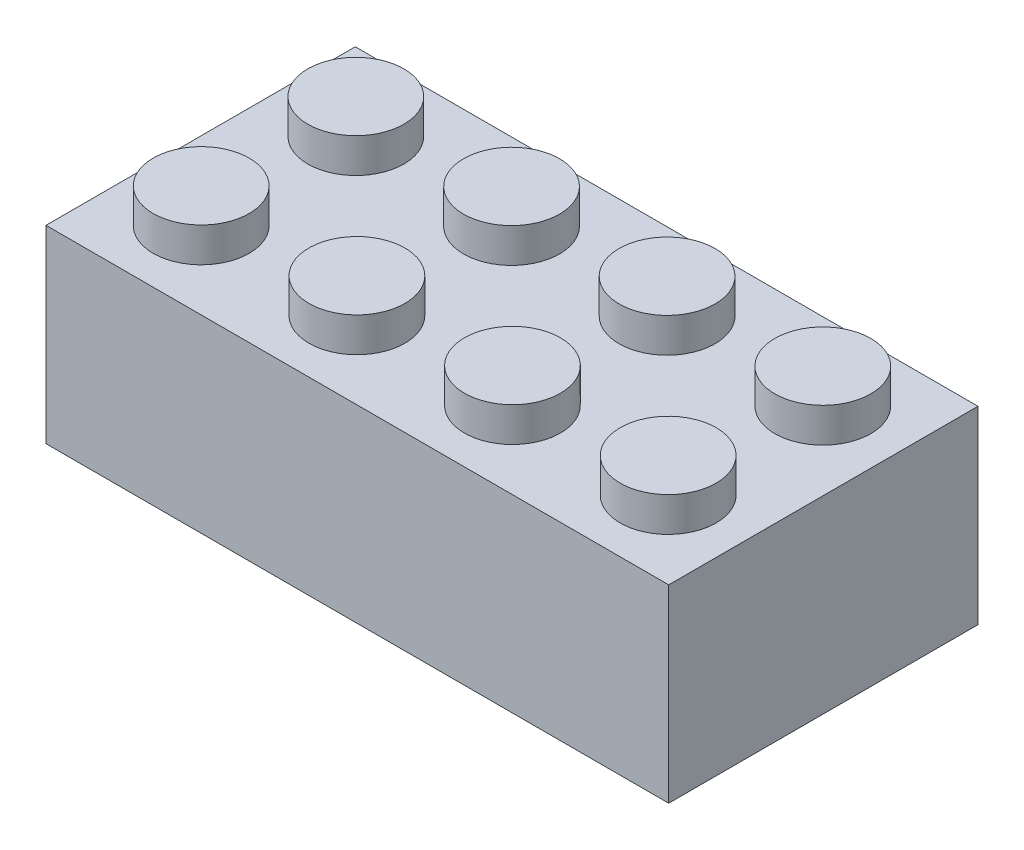
SolidWorks part; units mm, degrees
ref_plane "Front Plane" through (0, 0, 0) normal (0, 0, 1) x (1, 0, 0)
ref_plane "Top Plane" through (0, 0, 0) normal (0, 1, 0) x (1, 0, 0)
ref_plane "Right Plane" through (0, 0, 0) normal (1, 0, 0) x (0, 0, -1)
sketch "Sketch2" plane through (0, 0, 0) normal (0, 1, 0) x (1, 0, 0)
  line L1 (-15.885, 7.89) -> (15.885, 7.89)
  line L2 (-15.885, 7.89) -> (-15.885, -7.89)
  line L3 (-15.885, -7.89) -> (15.885, -7.89)
  line L4 (15.885, 7.89) -> (15.885, -7.89)
  line L5 (-15.885, 7.89) -> (15.885, -7.89) construction
  line L6 (-15.885, -7.89) -> (15.885, 7.89) construction
  point P0 (0, 0)
  dimension "D1" = 31.77
  dimension "D2" = 15.78
extrude "Boss-Extrude2" add sketch "Sketch2" against normal blind 9.65
sketch "Sketch3" plane through (0, 0, 0) normal (0, 1, 0) x (1, 0, 0)
  line L0 (0, 10.9518) -> (0, -11.5187) construction
  line L2 (-15.885, 7.89) -> (-15.885, -7.89) construction
  line L3 (-15.885, -7.89) -> (15.885, -7.89) construction
  line L4 (15.885, 7.89) -> (-15.885, 7.89) construction
  circle A0 centre (-11.9125, 3.945) radius 2.45
  circle A1 centre (-3.9675, 3.945) radius 2.45
  circle A2 centre (-3.9675, -3.945) radius 2.45
  circle A3 centre (-11.9125, -3.945) radius 2.45
  circle A4 centre (11.9125, -3.945) radius 2.45
  circle A5 centre (3.9675, -3.945) radius 2.45
  circle A6 centre (3.9675, 3.945) radius 2.45
  circle A7 centre (11.9125, 3.945) radius 2.45
  dimension "D1" = 4.9
  dimension "D2" = 4.9
  dimension "D3" = 4.9
  dimension "D4" = 4.9
  dimension "D6" = 3.945
  dimension "D7" = 7.945
  dimension "D8" = 3.9725
  dimension "D11" = 7.945
  dimension "D5" = 3.9725
  dimension "D9" = 3.945
  dimension "D10" = 3.945
  dimension "D12" = 3.945
extrude "Boss-Extrude3" add sketch "Sketch3" along normal blind 1.76
shell "Shell1" thickness 1.2
sketch "Sketch4" plane through (0, -1.2, 0) normal (0, -1, 0) x (1, 0, 0)
  line L1 (15.885, -7.89) -> (-15.885, -7.89) construction
  line L2 (-15.885, 7.89) -> (15.885, 7.89) construction
  circle A0 centre (0, 0) radius 3.215
  circle A1 centre (0, 0) radius 2.305
  circle A2 centre (7.945, 0) radius 3.215
  circle A3 centre (7.945, 0) radius 2.305
  circle A4 centre (-7.945, 0) radius 3.215
  circle A5 centre (-7.945, 0) radius 2.305
  dimension "D1" = 6.43
  dimension "D2" = 6.43
  dimension "D3" = 6.43
  dimension "D4" = 4.61
  dimension "D5" = 4.61
  dimension "D6" = 4.61
  dimension "D7" = 7.945
  dimension "D8" = 7.945
  dimension "D10" = 7.89
  dimension "D9" = 7.89
extrude "Boss-Extrude4" add sketch "Sketch4" along normal offset from surface (8.25 mm away) 0.2 up to face at (0, -9.65, 0)
